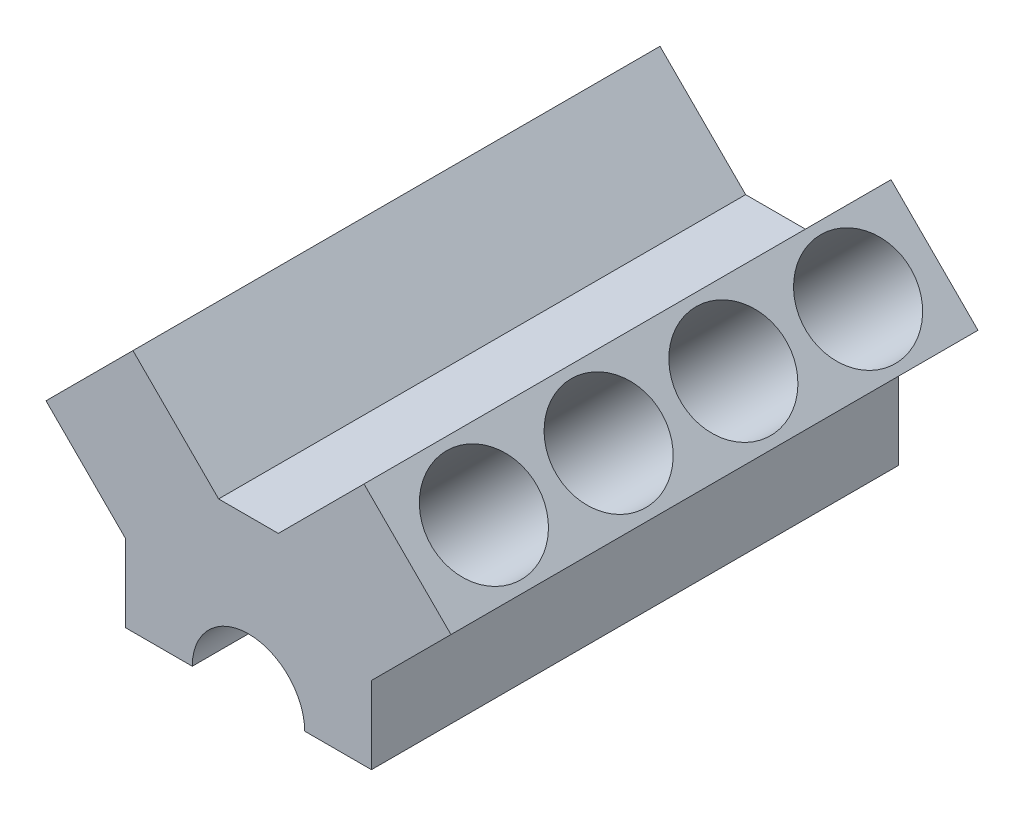
SolidWorks part; units mm, degrees
material "Alumina"
ref_plane "Front Plane" through (0, 0, 0) normal (0, 0, 1) x (1, 0, 0)
ref_plane "Top Plane" through (0, 0, 0) normal (0, 1, 0) x (1, 0, 0)
ref_plane "Right Plane" through (0, 0, 0) normal (1, 0, 0) x (0, 0, -1)
sketch "Sketch1" plane through (0, 0, 0) normal (0, 0, 1) x (1, 0, 0)
  line L0 (0, 0) -> (48.26, 0)
  line L1 (177.8, 0) -> (177.8, 55.88)
  line L2 (177.8, 55.88) -> (235.2736, 113.3536)
  line L3 (235.2736, 113.3536) -> (172.4118, 176.2154)
  line L6 (5.3882, 176.2154) -> (-57.4736, 113.3536)
  line L7 (-57.4736, 113.3536) -> (0, 55.88)
  line L8 (0, 55.88) -> (0, 0)
  line L9 (129.54, 0) -> (177.8, 0)
  line L10 (5.3882, 176.2154) -> (67.31, 114.2936)
  line L11 (172.4118, 176.2154) -> (110.49, 114.2936)
  line L12 (110.49, 114.2936) -> (67.31, 114.2936)
  arc A0 (129.54, 0) -> (48.26, 0) centre (88.9, 0) ccw
  dimension "D5" = 40.64
  dimension "D1" = 177.8
  dimension "D2" = 55.88
  dimension "D3" = 81.28
  dimension "D4" = 88.9
  dimension "D6" = 43.18
extrude "Boss-Extrude1" add sketch "Sketch1" along normal blind 381
sketch "Sketch2" plane through (174.3136, 174.3136, 0) normal (0.7071, 0.7071, 0) x (0, 0, -1)
  line L0 (-325.755, -41.7576) -> (-235.585, -41.7576) construction
  line L1 (-381, -86.2105) -> (-381, 2.6895) construction
  line L2 (0, -86.2105) -> (0, 2.6895) construction
  circle A0 centre (-325.755, -41.7576) radius 38.1
  circle A1 centre (-235.585, -41.7576) radius 38.1
  circle A2 centre (-145.415, -41.7576) radius 38.1
  circle A3 centre (-55.245, -41.7576) radius 38.1
  dimension "D3" = 55.245
  dimension "D5" = 76.2
  dimension "D2" = 90.17
  dimension "D4" = 55.245
  dimension "D1" = 4
extrude "Cut-Extrude2" cut sketch "Sketch2" against normal blind 165.1
sketch "Sketch3" plane through (-85.4136, 85.4136, 0) normal (-0.7071, 0.7071, 0) x (0, 0, 1)
  line L0 (55.245, 83.3118) -> (145.415, 83.3118) construction
  line L1 (0, 128.4131) -> (0, 39.5131) construction
  line L2 (381, 128.4131) -> (381, 39.5131) construction
  circle A0 centre (55.245, 83.3118) radius 38.1
  circle A1 centre (145.415, 83.3118) radius 38.1
  circle A2 centre (235.585, 83.3118) radius 38.1
  circle A3 centre (325.755, 83.3118) radius 38.1
  point P2 (0, 0)
  dimension "D3" = 55.245
  dimension "D4" = 76.2
  dimension "D2" = 90.17
  dimension "D5" = 55.245
  dimension "D1" = 4
extrude "Cut-Extrude3" cut sketch "Sketch3" against normal blind 165.1
